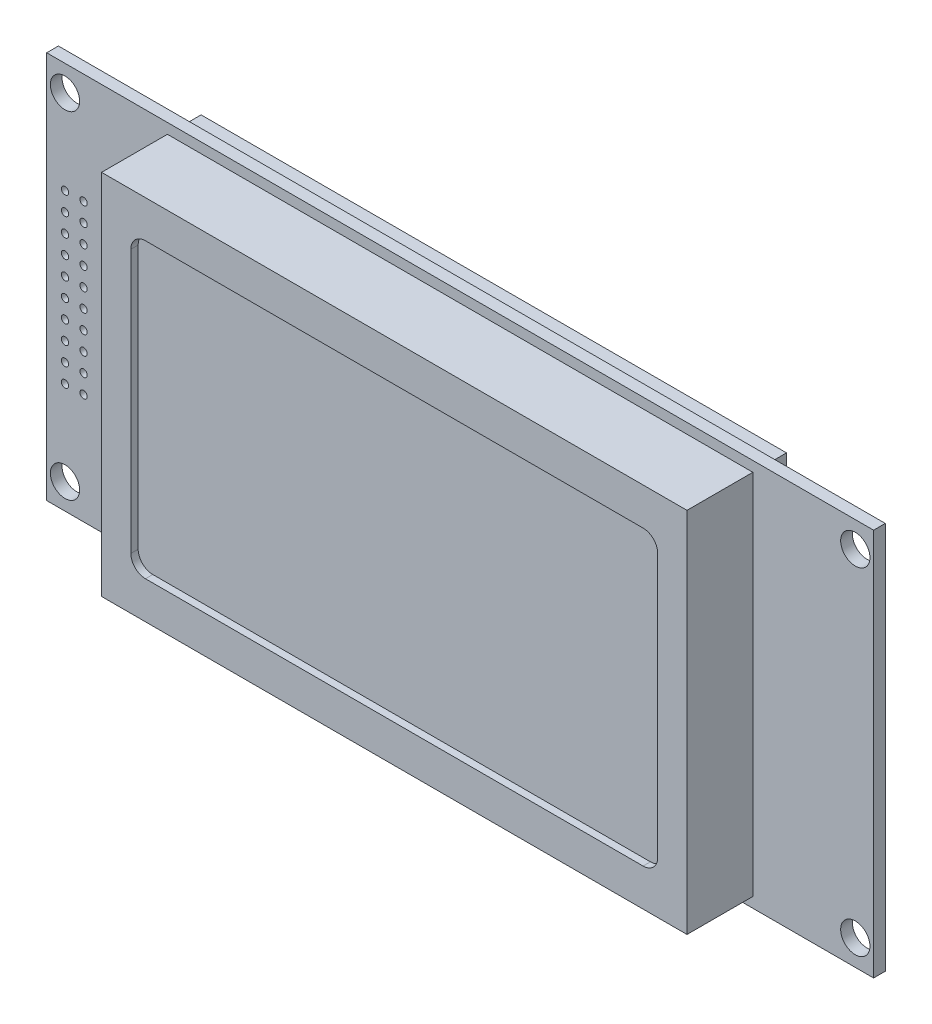
SolidWorks part; units mm, degrees
ref_plane "Plan de face" through (0, 0, 0) normal (0, 0, 1) x (1, 0, 0)
ref_plane "Plan de dessus" through (0, 0, 0) normal (0, 1, 0) x (1, 0, 0)
ref_plane "Plan de droite" through (0, 0, 0) normal (1, 0, 0) x (0, 0, -1)
sketch "Esquisse1" plane through (0, 0, 0) normal (0, 0, 1) x (1, 0, 0)
  line L0 (-56.5, 0) -> (56.5, 0) construction
  line L1 (-56.5, 26.5) -> (56.5, 26.5)
  line L2 (-56.5, 26.5) -> (-56.5, -26.5)
  line L3 (-56.5, -26.5) -> (56.5, -26.5)
  line L4 (56.5, 26.5) -> (56.5, -26.5)
  line L5 (0, 26.5) -> (0, -26.5) construction
  line L6 (-54, 23) -> (-54, -23) construction
  line L7 (-54, -23) -> (54, -23) construction
  circle A0 centre (-54, 23) radius 2
  circle A1 centre (-54, -23) radius 2
  circle A2 centre (54, -23) radius 2
  circle A3 centre (54, 23) radius 2
  circle A4 centre (-54, 11.43) radius 0.5
  circle A5 centre (-51.46, 11.43) radius 0.5
  circle A6 centre (-51.46, 8.89) radius 0.5
  circle A7 centre (-51.46, 6.35) radius 0.5
  circle A8 centre (-51.46, 3.81) radius 0.5
  circle A9 centre (-51.46, 1.27) radius 0.5
  circle A10 centre (-51.46, -1.27) radius 0.5
  circle A11 centre (-51.46, -3.81) radius 0.5
  circle A12 centre (-51.46, -6.35) radius 0.5
  circle A13 centre (-51.46, -8.89) radius 0.5
  circle A14 centre (-51.46, -11.43) radius 0.5
  circle A15 centre (-54, 8.89) radius 0.5
  circle A16 centre (-54, 6.35) radius 0.5
  circle A17 centre (-54, 3.81) radius 0.5
  circle A18 centre (-54, 1.27) radius 0.5
  circle A19 centre (-54, -1.27) radius 0.5
  circle A20 centre (-54, -3.81) radius 0.5
  circle A21 centre (-54, -6.35) radius 0.5
  circle A22 centre (-54, -8.89) radius 0.5
  circle A23 centre (-54, -11.43) radius 0.5
  point P10 (-54, 0)
  point P11 (0, -23)
  point P20 (0, 0)
  dimension "D5" = 4
  dimension "D7" = 1
  dimension "D1" = 53
  dimension "D2" = 113
  dimension "D3" = 46
  dimension "D4" = 108
  dimension "D6" = 2.5
  dimension "D8" = 11.43
  dimension "D11" = 108
  dimension "D9" = 2
  dimension "D10" = 10
extrude "Boss.-Extru.1" add sketch "Esquisse1" along normal blind 1.6
sketch "Esquisse2" plane through (0, 0, 1.6) normal (0, 0, 1) x (1, 0, 0)
  line L0 (0, 26.5) -> (0, -26.5) construction
  line L1 (56.5, 26.5) -> (-56.5, 26.5) construction
  line L2 (-56.5, -26.5) -> (56.5, -26.5) construction
  line L4 (-40, -25.1) -> (40, -25.1)
  line L5 (-40, -25.1) -> (-40, 25.1)
  line L6 (-40, 25.1) -> (40, 25.1)
  line L7 (40, -25.1) -> (40, 25.1)
  line L8 (-40, -25.1) -> (40, 25.1) construction
  line L9 (-40, 25.1) -> (40, -25.1) construction
  point P7 (0, 0)
  dimension "D1" = 50.2
  dimension "D2" = 80
extrude "Boss.-Extru.2" add sketch "Esquisse2" along normal blind 9
sketch "Esquisse4" plane through (0, 0, 10.6) normal (0, 0, 1) x (1, 0, 0)
  line L1 (34, -20) -> (-34, -20)
  line L2 (36, -18) -> (36, 18)
  line L3 (34, 20) -> (-34, 20)
  line L4 (-36, -18) -> (-36, 18)
  line L5 (36, -20) -> (-36, 20) construction
  line L6 (36, 20) -> (-36, -20) construction
  arc A0 (-34, -20) -> (-36, -18) centre (-34, -18) cw
  arc A1 (34, -20) -> (36, -18) centre (34, -18) ccw
  arc A2 (36, 18) -> (34, 20) centre (34, 18) ccw
  arc A3 (-34, 20) -> (-36, 18) centre (-34, 18) ccw
  point P0 (0, 0)
  dimension "D3" = 2
  dimension "D1" = 72
  dimension "D2" = 40
extrude "Enlèv. mat.-Extru.1" cut sketch "Esquisse4" against normal blind 1
sketch "Esquisse6" plane through (0, 0, 0) normal (0, 0, -1) x (-1, 0, 0)
  line L1 (-40, 25.1) -> (40, 25.1)
  line L2 (-40, 25.1) -> (-40, 22.6716)
  line L3 (-40, 22.6716) -> (40, 22.6716)
  line L4 (40, 25.1) -> (40, 22.6716)
  line L5 (-40, -25.1) -> (40, -25.1)
  line L6 (-40, -25.1) -> (-40, -23.3251)
  line L7 (-40, -23.3251) -> (40, -23.3251)
  line L8 (40, -25.1) -> (40, -23.3251)
extrude "Boss.-Extru.3" add sketch "Esquisse6" along normal blind 3
equation "\"D8@Esquisse1\"=22.86/2"
